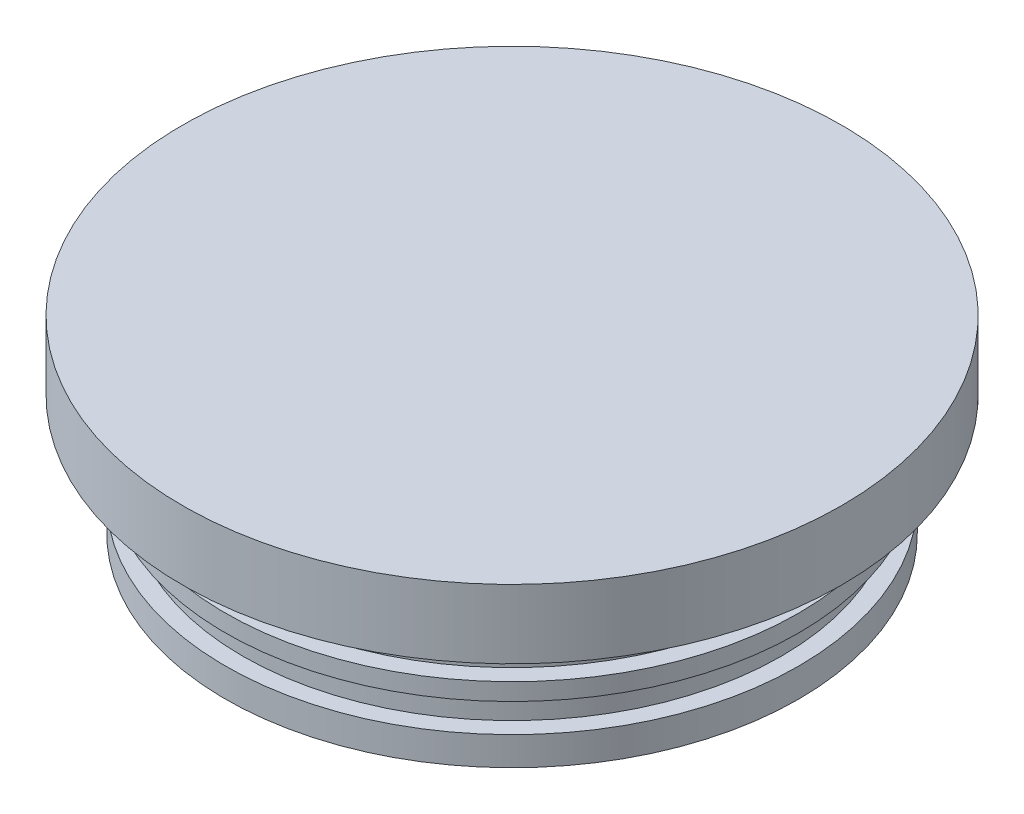
SolidWorks part; units mm, degrees
ref_plane "Plan de face" through (0, 0, 0) normal (0, 0, 1) x (1, 0, 0)
ref_plane "Plan de dessus" through (0, 0, 0) normal (0, 1, 0) x (1, 0, 0)
ref_plane "Plan de droite" through (0, 0, 0) normal (1, 0, 0) x (0, 0, -1)
sketch "Esquisse1" plane through (0, 0, 0) normal (0, 0, 1) x (1, 0, 0)
  line L0 (0, 0) -> (45, 0)
  line L1 (45, 0) -> (45, -27)
  line L2 (45, -27) -> (50, -27)
  line L3 (50, -27) -> (50, -22)
  line L4 (50, -6) -> (57.5, -6)
  line L5 (57.5, -6) -> (57.5, 6)
  line L6 (57.5, 6) -> (0, 6)
  line L7 (0, 6) -> (0, 0) construction
  line L8 (50, -22) -> (47, -22)
  line L9 (47, -22) -> (47, -17)
  line L10 (47, -17) -> (50, -17)
  line L11 (50, -14) -> (47, -14)
  line L12 (47, -14) -> (47, -9)
  line L13 (47, -9) -> (50, -9)
  line L14 (50, -9) -> (50, -6)
  line L15 (50, -17) -> (50, -14)
  line L16 (0, 0) -> (0, 6)
  dimension "D1" = 100
  dimension "D2" = 5
  dimension "D3" = 21
  dimension "D4" = 115
  dimension "D5" = 5
  dimension "D6" = 5
  dimension "D7" = 5
  dimension "D8" = 3
  dimension "D9" = 3
  dimension "D10" = 6
  dimension "D11" = 12
revolve "Révolution1" add sketch "Esquisse1" angle 360 about L16
